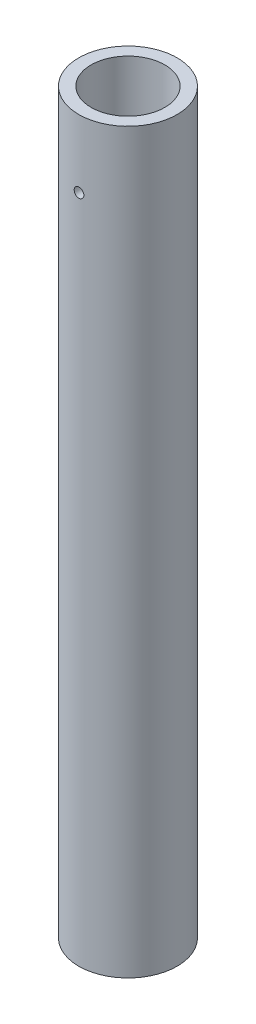
SolidWorks part; units mm, degrees
material "Thornel Mat VMA"
ref_plane "Front Plane" through (0, 0, 0) normal (0, 0, 1) x (1, 0, 0)
ref_plane "Top Plane" through (0, 0, 0) normal (0, 1, 0) x (1, 0, 0)
ref_plane "Right Plane" through (0, 0, 0) normal (1, 0, 0) x (0, 0, -1)
sketch "Sketch2" plane through (0, 0, 0) normal (0, 1, 0) x (1, 0, 0)
  circle A0 centre (0, 0) radius 10.16
  circle A1 centre (0, 0) radius 7.62
  dimension "D1" = 20.32
  dimension "D2" = 15.24
extrude "Boss-Extrude1" add sketch "Sketch2" along normal blind 152.4
sketch "Sketch3" plane through (0, 0, 0) normal (0, 0, 1) x (1, 0, 0)
  line L0 (10.16, 152.4) -> (-10.16, 152.4) construction
  line L1 (-10.16, 152.4) -> (10.16, 152.4)
  circle A0 centre (0, 138.43) radius 1
  point P9 (0, 152.4)
  dimension "D1" = 2
  dimension "D2" = 13.97
extrude "Cut-Extrude1" cut sketch "Sketch3" against normal through all both and the other way through all contours A0
sketch "Sketch4" plane through (0, 0, 0) normal (0, 0, 1) x (1, 0, 0)
  line L1 (-2.54, 70.4578) -> (2.54, 70.4578)
  line L2 (-2.54, 70.4578) -> (-2.54, 45.0578)
  line L3 (-2.54, 45.0578) -> (2.54, 45.0578)
  line L4 (2.54, 70.4578) -> (2.54, 45.0578)
  point P4 (0, 45.0578)
  dimension "D1" = 5.08
  dimension "D2" = 25.4
extrude "Cut-Extrude2" cut sketch "Sketch4" against normal through all
